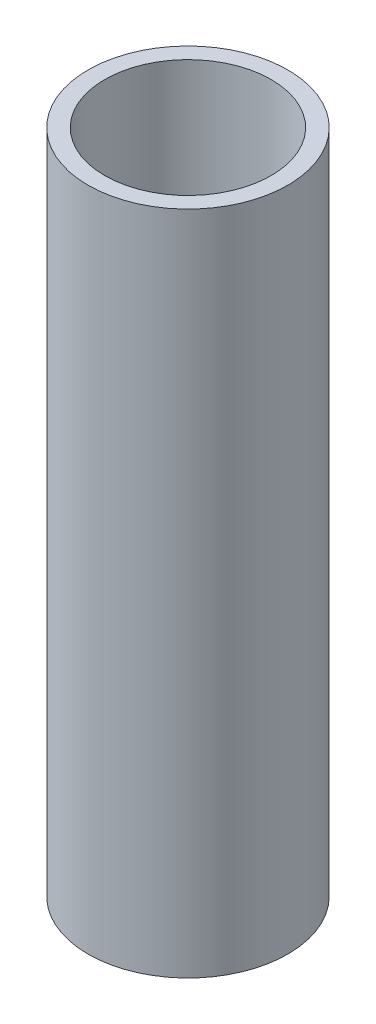
SolidWorks part; units mm, degrees
ref_plane "Front Plane" through (0, 0, 0) normal (0, 0, 1) x (1, 0, 0)
ref_plane "Top Plane" through (0, 0, 0) normal (0, 1, 0) x (1, 0, 0)
ref_plane "Right Plane" through (0, 0, 0) normal (1, 0, 0) x (0, 0, -1)
sketch "Sketch1" plane through (0, 0, 0) normal (0, 1, 0) x (1, 0, 0)
  circle A0 centre (0, 0) radius 12.5
  circle A1 centre (0, 0) radius 15
extrude "Boss-Extrude1" add sketch "Sketch1" along normal blind 100
